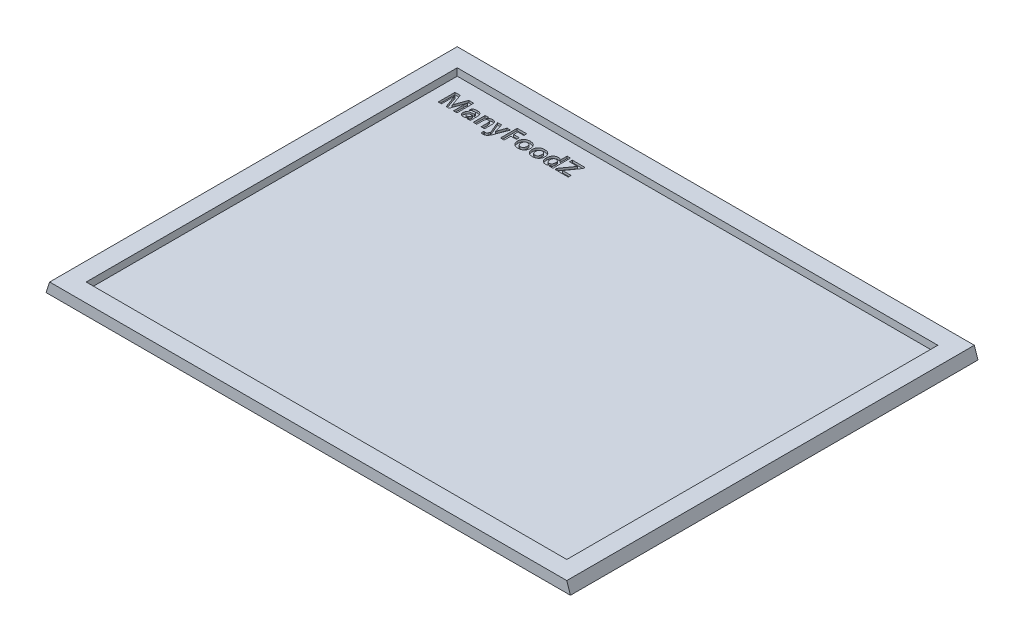
SolidWorks part; units mm, degrees
ref_plane "前视基准面" through (0, 0, 0) normal (0, 0, 1) x (1, 0, 0)
ref_plane "上视基准面" through (0, 0, 0) normal (0, 1, 0) x (1, 0, 0)
ref_plane "右视基准面" through (0, 0, 0) normal (1, 0, 0) x (0, 0, -1)
sketch "Sketch1" plane through (0, 0, 0) normal (0, 1, 0) x (1, 0, 0)
  line L0 (-71.8, 55.8) -> (71.8, -55.8) construction
  line L1 (-71.8, 55.8) -> (71.8, 55.8)
  line L2 (-71.8, 55.8) -> (-71.8, -55.8)
  line L3 (-71.8, -55.8) -> (71.8, -55.8)
  line L4 (71.8, 55.8) -> (71.8, -55.8)
  dimension "D1" = 143.6
  dimension "D2" = 111.6
extrude "Boss-Extrude1" add sketch "Sketch1" along normal blind 3
sketch "Sketch2" plane through (0, 0, 55.8) normal (0, 0, 1) x (1, 0, 0)
  line L0 (71.8, 0) -> (70.8, 3)
  line L1 (-71.8, 3) -> (71.8, 3) construction
  line L2 (70.8, 3) -> (71.8, 3)
  line L3 (71.8, 3) -> (71.8, 0)
  line L4 (0, 0) -> (0, 3) construction
  line L5 (-71.8, 3) -> (-71.8, 0)
  line L6 (-70.8, 3) -> (-71.8, 3)
  line L7 (-71.8, 0) -> (-70.8, 3)
  dimension "D1" = 1
extrude "Cut-Extrude1" cut sketch "Sketch2" against normal up to next
sketch "Sketch3" plane through (0, 3, 0) normal (0, 1, 0) x (1, 0, 0)
  line L0 (70.8, 55.8) -> (-70.8, 55.8) construction
  line L1 (-65.8, -50.8) -> (65.8, -50.8)
  line L2 (-65.8, -50.8) -> (-65.8, 50.8)
  line L3 (-65.8, 50.8) -> (65.8, 50.8)
  line L4 (65.8, -50.8) -> (65.8, 50.8)
  line L5 (-65.8, -50.8) -> (65.8, 50.8) construction
  line L6 (-65.8, 50.8) -> (65.8, -50.8) construction
  line L7 (70.8, 55.8) -> (70.8, -55.8) construction
  point P0 (0, 0)
  dimension "D1" = 5
  dimension "D2" = 5
extrude "Cut-Extrude2" cut sketch "Sketch3" against normal offset from surface (2 mm away) 1 up to face at (0, 0, 0)
sketch "Sketch4" plane through (0, 1, 0) normal (0, 1, 0) x (1, 0, 0)
  text T0 "<b>ManyFoodZ</b>" font "微软雅黑" height in points 16
extrude "Cut-Extrude3" cut sketch "Sketch4" against normal offset from surface (0.6 mm away) 0.4 up to face at (0, 0, 0)
